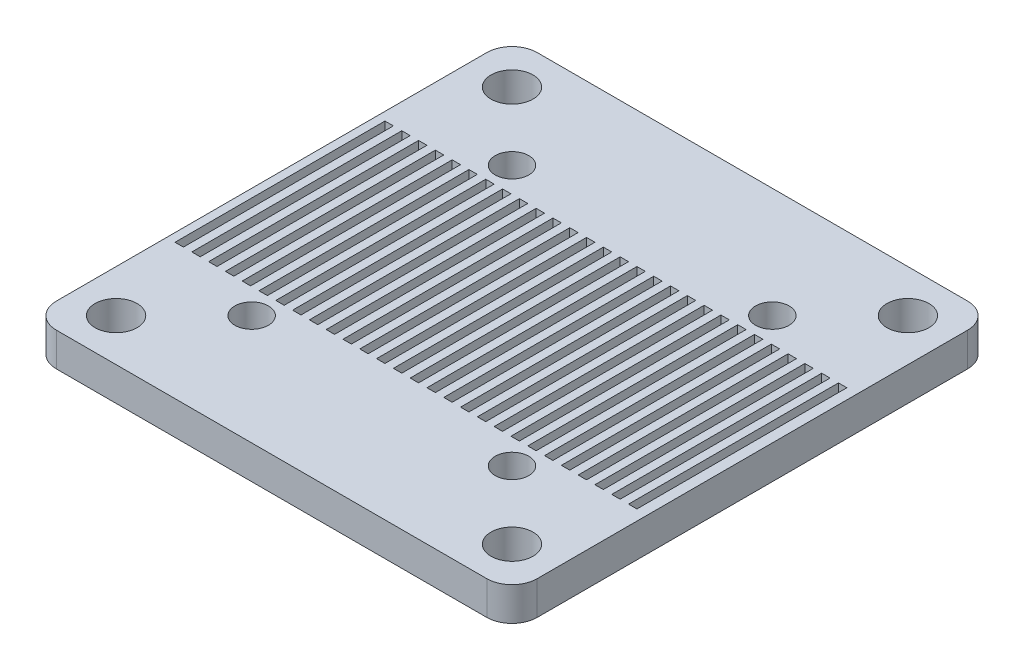
SolidWorks part; units mm, degrees
ref_plane "Front Plane" through (0, 0, 0) normal (0, 0, 1) x (1, 0, 0)
ref_plane "Top Plane" through (0, 0, 0) normal (0, 1, 0) x (1, 0, 0)
ref_plane "Right Plane" through (0, 0, 0) normal (1, 0, 0) x (0, 0, -1)
sketch "Sketch1" plane through (0, 0, 0) normal (0, 1, 0) x (1, 0, 0)
  line L1 (25.625, 28.625) -> (-25.625, 28.625)
  line L2 (28.625, 25.625) -> (28.625, -25.625)
  line L3 (25.625, -28.625) -> (-25.625, -28.625)
  line L4 (-28.625, 25.625) -> (-28.625, -25.625)
  line L5 (28.625, 28.625) -> (-28.625, -28.625) construction
  line L6 (28.625, -28.625) -> (-28.625, 28.625) construction
  line L7 (23.57, -23.57) -> (-23.57, -23.57) construction
  line L8 (23.57, -23.57) -> (23.57, 23.57) construction
  line L9 (23.57, 23.57) -> (-23.57, 23.57) construction
  line L10 (-23.57, -23.57) -> (-23.57, 23.57) construction
  line L11 (23.57, -23.57) -> (-23.57, 23.57) construction
  line L12 (23.57, 23.57) -> (-23.57, -23.57) construction
  line L13 (15.5, 15.5) -> (-15.5, 15.5) construction
  line L14 (15.5, 15.5) -> (15.5, -15.5) construction
  line L15 (15.5, -15.5) -> (-15.5, -15.5) construction
  line L16 (-15.5, 15.5) -> (-15.5, -15.5) construction
  line L17 (15.5, 15.5) -> (-15.5, -15.5) construction
  line L18 (15.5, -15.5) -> (-15.5, 15.5) construction
  circle A0 centre (-15.5, 15.5) radius 2
  circle A1 centre (-23.57, 23.57) radius 2.5
  circle A2 centre (23.57, 23.57) radius 2.5
  circle A3 centre (15.5, 15.5) radius 2
  circle A4 centre (15.5, -15.5) radius 2
  circle A5 centre (-15.5, -15.5) radius 2
  circle A6 centre (-23.57, -23.57) radius 2.5
  circle A7 centre (23.57, -23.57) radius 2.5
  arc A8 (25.625, 28.625) -> (28.625, 25.625) centre (25.625, 25.625) cw
  arc A9 (28.625, -25.625) -> (25.625, -28.625) centre (25.625, -25.625) cw
  arc A10 (-25.625, -28.625) -> (-28.625, -25.625) centre (-25.625, -25.625) cw
  arc A11 (-25.625, 28.625) -> (-28.625, 25.625) centre (-25.625, 25.625) ccw
  point P0 (0, 0)
  point P5 (0, 0)
  point P11 (0, 0)
  dimension "D7" = 5
  dimension "D8" = 5
  dimension "D9" = 4
  dimension "D10" = 4
  dimension "D11" = 4
  dimension "D12" = 4
  dimension "D13" = 5
  dimension "D14" = 5
  dimension "D15" = 3
  dimension "D1" = 57.25
  dimension "D2" = 57.25
  dimension "D3" = 47.14
  dimension "D4" = 47.14
  dimension "D5" = 31
  dimension "D6" = 31
extrude "Boss-Extrude1" add sketch "Sketch1" along normal blind 4
sketch "Sketch2" plane through (0, 4, 0) normal (0, 1, 0) x (1, 0, 0)
  line L0 (-28.625, 25.625) -> (-28.625, -25.625) construction
  line L3 (-27.625, 12.5) -> (-26.625, 12.5)
  line L4 (-27.625, 12.5) -> (-27.625, -12.5)
  line L5 (-27.625, -12.5) -> (-26.625, -12.5)
  line L6 (-26.625, 12.5) -> (-26.625, -12.5)
  line L7 (-25.625, -12.5) -> (-24.625, -12.5)
  line L8 (-24.625, 12.5) -> (-24.625, -12.5)
  line L9 (-25.625, 12.5) -> (-25.625, -12.5)
  line L10 (-25.625, 12.5) -> (-24.625, 12.5)
  line L11 (-23.625, -12.5) -> (-22.625, -12.5)
  line L12 (-22.625, 12.5) -> (-22.625, -12.5)
  line L13 (-23.625, 12.5) -> (-23.625, -12.5)
  line L14 (-23.625, 12.5) -> (-22.625, 12.5)
  line L15 (-21.625, -12.5) -> (-20.625, -12.5)
  line L16 (-20.625, 12.5) -> (-20.625, -12.5)
  line L17 (-21.625, 12.5) -> (-21.625, -12.5)
  line L18 (-21.625, 12.5) -> (-20.625, 12.5)
  line L19 (-19.625, -12.5) -> (-18.625, -12.5)
  line L20 (-18.625, 12.5) -> (-18.625, -12.5)
  line L21 (-19.625, 12.5) -> (-19.625, -12.5)
  line L22 (-19.625, 12.5) -> (-18.625, 12.5)
  line L23 (-17.625, -12.5) -> (-16.625, -12.5)
  line L24 (-16.625, 12.5) -> (-16.625, -12.5)
  line L25 (-17.625, 12.5) -> (-17.625, -12.5)
  line L26 (-17.625, 12.5) -> (-16.625, 12.5)
  line L27 (-15.625, -12.5) -> (-14.625, -12.5)
  line L28 (-14.625, 12.5) -> (-14.625, -12.5)
  line L29 (-15.625, 12.5) -> (-15.625, -12.5)
  line L30 (-15.625, 12.5) -> (-14.625, 12.5)
  line L31 (-13.625, -12.5) -> (-12.625, -12.5)
  line L32 (-12.625, 12.5) -> (-12.625, -12.5)
  line L33 (-13.625, 12.5) -> (-13.625, -12.5)
  line L34 (-13.625, 12.5) -> (-12.625, 12.5)
  line L35 (-11.625, -12.5) -> (-10.625, -12.5)
  line L36 (-10.625, 12.5) -> (-10.625, -12.5)
  line L37 (-11.625, 12.5) -> (-11.625, -12.5)
  line L38 (-11.625, 12.5) -> (-10.625, 12.5)
  line L39 (-9.625, -12.5) -> (-8.625, -12.5)
  line L40 (-8.625, 12.5) -> (-8.625, -12.5)
  line L41 (-9.625, 12.5) -> (-9.625, -12.5)
  line L42 (-9.625, 12.5) -> (-8.625, 12.5)
  line L43 (-7.625, -12.5) -> (-6.625, -12.5)
  line L44 (-6.625, 12.5) -> (-6.625, -12.5)
  line L45 (-7.625, 12.5) -> (-7.625, -12.5)
  line L46 (-7.625, 12.5) -> (-6.625, 12.5)
  line L47 (-5.625, -12.5) -> (-4.625, -12.5)
  line L48 (-4.625, 12.5) -> (-4.625, -12.5)
  line L49 (-5.625, 12.5) -> (-5.625, -12.5)
  line L50 (-5.625, 12.5) -> (-4.625, 12.5)
  line L51 (-3.625, -12.5) -> (-2.625, -12.5)
  line L52 (-2.625, 12.5) -> (-2.625, -12.5)
  line L53 (-3.625, 12.5) -> (-3.625, -12.5)
  line L54 (-3.625, 12.5) -> (-2.625, 12.5)
  line L55 (-1.625, -12.5) -> (-0.625, -12.5)
  line L56 (-0.625, 12.5) -> (-0.625, -12.5)
  line L57 (-1.625, 12.5) -> (-1.625, -12.5)
  line L58 (-1.625, 12.5) -> (-0.625, 12.5)
  line L59 (0.375, -12.5) -> (1.375, -12.5)
  line L60 (1.375, 12.5) -> (1.375, -12.5)
  line L61 (0.375, 12.5) -> (0.375, -12.5)
  line L62 (0.375, 12.5) -> (1.375, 12.5)
  line L63 (2.375, -12.5) -> (3.375, -12.5)
  line L64 (3.375, 12.5) -> (3.375, -12.5)
  line L65 (2.375, 12.5) -> (2.375, -12.5)
  line L66 (2.375, 12.5) -> (3.375, 12.5)
  line L67 (4.375, -12.5) -> (5.375, -12.5)
  line L68 (5.375, 12.5) -> (5.375, -12.5)
  line L69 (4.375, 12.5) -> (4.375, -12.5)
  line L70 (4.375, 12.5) -> (5.375, 12.5)
  line L71 (6.375, -12.5) -> (7.375, -12.5)
  line L72 (7.375, 12.5) -> (7.375, -12.5)
  line L73 (6.375, 12.5) -> (6.375, -12.5)
  line L74 (6.375, 12.5) -> (7.375, 12.5)
  line L75 (8.375, -12.5) -> (9.375, -12.5)
  line L76 (9.375, 12.5) -> (9.375, -12.5)
  line L77 (8.375, 12.5) -> (8.375, -12.5)
  line L78 (8.375, 12.5) -> (9.375, 12.5)
  line L79 (10.375, -12.5) -> (11.375, -12.5)
  line L80 (11.375, 12.5) -> (11.375, -12.5)
  line L81 (10.375, 12.5) -> (10.375, -12.5)
  line L82 (10.375, 12.5) -> (11.375, 12.5)
  line L83 (12.375, -12.5) -> (13.375, -12.5)
  line L84 (13.375, 12.5) -> (13.375, -12.5)
  line L85 (12.375, 12.5) -> (12.375, -12.5)
  line L86 (12.375, 12.5) -> (13.375, 12.5)
  line L87 (14.375, -12.5) -> (15.375, -12.5)
  line L88 (15.375, 12.5) -> (15.375, -12.5)
  line L89 (14.375, 12.5) -> (14.375, -12.5)
  line L90 (14.375, 12.5) -> (15.375, 12.5)
  line L91 (16.375, -12.5) -> (17.375, -12.5)
  line L92 (17.375, 12.5) -> (17.375, -12.5)
  line L93 (16.375, 12.5) -> (16.375, -12.5)
  line L94 (16.375, 12.5) -> (17.375, 12.5)
  line L95 (18.375, -12.5) -> (19.375, -12.5)
  line L96 (19.375, 12.5) -> (19.375, -12.5)
  line L97 (18.375, 12.5) -> (18.375, -12.5)
  line L98 (18.375, 12.5) -> (19.375, 12.5)
  line L99 (20.375, -12.5) -> (21.375, -12.5)
  line L100 (21.375, 12.5) -> (21.375, -12.5)
  line L101 (20.375, 12.5) -> (20.375, -12.5)
  line L102 (20.375, 12.5) -> (21.375, 12.5)
  line L103 (22.375, -12.5) -> (23.375, -12.5)
  line L104 (23.375, 12.5) -> (23.375, -12.5)
  line L105 (22.375, 12.5) -> (22.375, -12.5)
  line L106 (22.375, 12.5) -> (23.375, 12.5)
  line L107 (24.375, -12.5) -> (25.375, -12.5)
  line L108 (25.375, 12.5) -> (25.375, -12.5)
  line L109 (24.375, 12.5) -> (24.375, -12.5)
  line L110 (24.375, 12.5) -> (25.375, 12.5)
  line L111 (26.375, -12.5) -> (27.375, -12.5)
  line L112 (27.375, 12.5) -> (27.375, -12.5)
  line L113 (26.375, 12.5) -> (26.375, -12.5)
  line L114 (26.375, 12.5) -> (27.375, 12.5)
  dimension "D1" = 1
  dimension "D2" = 1
  dimension "D3" = 12.5
  dimension "D4" = 25
  dimension "D5" = 28
extrude "Cut-Extrude1" cut sketch "Sketch2" against normal blind 1
